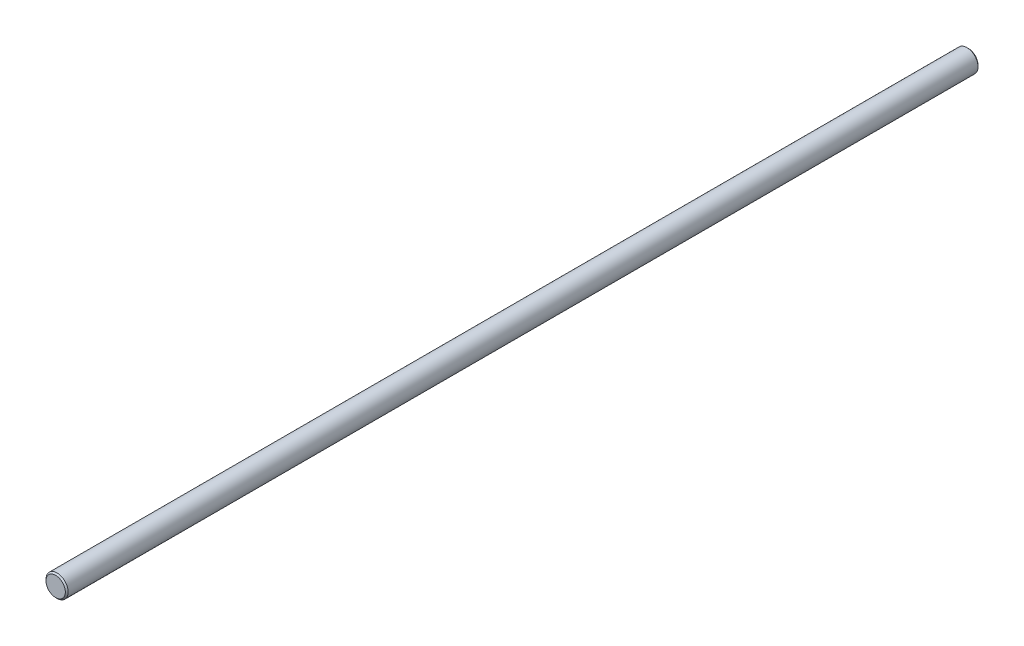
SolidWorks part; units mm, degrees
ref_plane "Front Plane" through (0, 0, 0) normal (0, 0, 1) x (1, 0, 0)
ref_plane "Top Plane" through (0, 0, 0) normal (0, 1, 0) x (1, 0, 0)
ref_plane "Right Plane" through (0, 0, 0) normal (1, 0, 0) x (0, 0, -1)
ref_plane "Plane1" through (0, 0, 0) normal (0, -1, 0) x (1, 0, 0)
sketch "Sketch1" plane through (0, 0, 0) normal (0, -1, 0) x (1, 0, 0)
  line L0 (3.5, 330) -> (0, 330)
  line L1 (0, 330) -> (0, 0)
  line L2 (0, 0) -> (3.5, 0)
  line L3 (3.5, 0) -> (4, 0.5)
  line L4 (4, 0.5) -> (4, 329.5)
  line L5 (4, 329.5) -> (3.5, 330)
  line L6 (0, 330) -> (0, 0) construction
revolve "Revolve1" add sketch "Sketch1" angle 360 about L6
